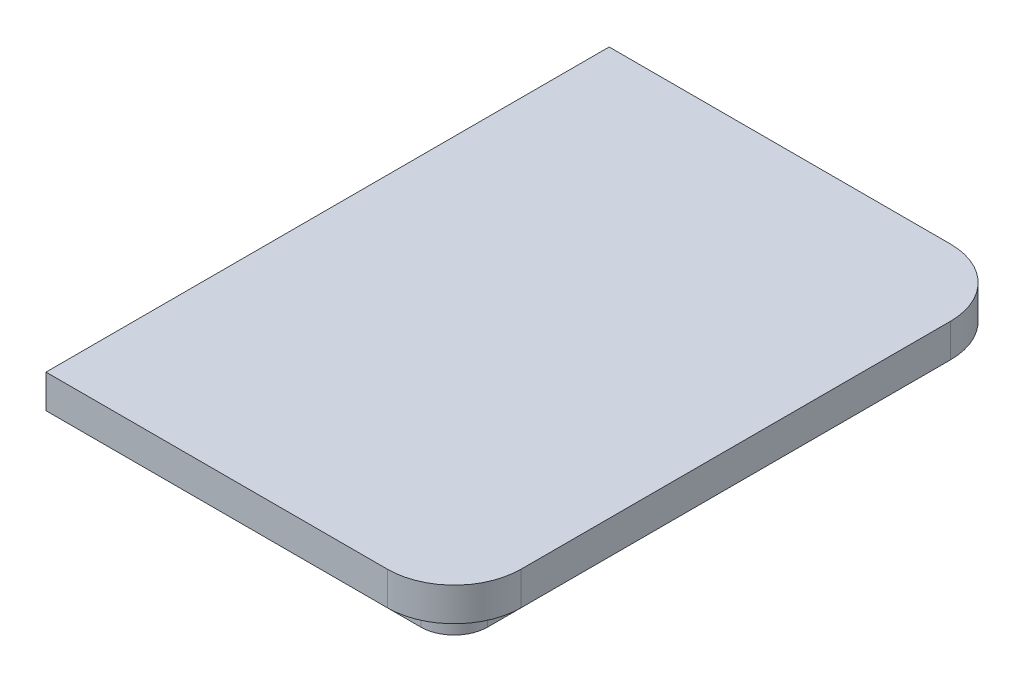
SolidWorks part; units mm, degrees
ref_plane "Alzado" through (0, 0, 0) normal (0, 0, 1) x (1, 0, 0)
ref_plane "Planta" through (0, 0, 0) normal (0, 1, 0) x (1, 0, 0)
ref_plane "Vista lateral" through (0, 0, 0) normal (1, 0, 0) x (0, 0, -1)
sketch "Croquis1" plane through (0, 0, 0) normal (0, 1, 0) x (1, 0, 0)
  line L1 (-30.5, -42.075) -> (20.5, -42.075)
  line L2 (-30.5, -42.075) -> (-30.5, 42.075)
  line L3 (-30.5, 42.075) -> (20.5, 42.075)
  line L4 (30.5, -32.075) -> (30.5, 32.075)
  line L5 (-30.5, -42.075) -> (30.5, 42.075) construction
  line L6 (-30.5, 42.075) -> (30.5, -42.075) construction
  arc A0 (20.5, -42.075) -> (30.5, -32.075) centre (20.5, -32.075) ccw
  arc A1 (30.5, 32.075) -> (20.5, 42.075) centre (20.5, 32.075) ccw
  point P0 (0, 0)
  dimension "D3" = 10
  dimension "D4" = 10
  dimension "D1" = 61
  dimension "D2" = 84.15
extrude "Saliente-Extruir1" add sketch "Croquis1" along normal blind 5
sketch "Croquis2" plane through (0, 0, 0) normal (0, 1, 0) x (1, 0, 0)
  line L4 (-30.5, -32.075) -> (20.5, -32.075)
  line L5 (20.5, -32.075) -> (20.5, 32.075)
  line L6 (20.5, 32.075) -> (-30.5, 32.075)
  line L7 (-30.5, 37.075) -> (-30.5, 32.075)
  line L12 (-30.5, -32.075) -> (-30.5, -37.075)
  line L29 (-25.5, 37.075) -> (-25.5, -37.075)
  line L30 (-25.5, -37.075) -> (20.5, -37.075)
  line L31 (25.5, -32.075) -> (25.5, 32.075)
  line L32 (20.5, 37.075) -> (-25.5, 37.075)
  line L34 (-30.5, -37.075) -> (20.5, -37.075)
  line L35 (25.5, -32.075) -> (25.5, 32.075)
  line L36 (20.5, 37.075) -> (-30.5, 37.075)
  arc A3 (20.5, -32.075) -> (20.5, -32.075) centre (20.5, -32.075) ccw
  arc A6 (20.5, 32.075) -> (20.5, 32.075) centre (20.5, 32.075) ccw
  arc A14 (20.5, -37.075) -> (25.5, -32.075) centre (20.5, -32.075) ccw
  arc A15 (25.5, 32.075) -> (20.5, 37.075) centre (20.5, 32.075) ccw
  arc A16 (20.5, -37.075) -> (25.5, -32.075) centre (20.5, -32.075) ccw
  arc A17 (25.5, 32.075) -> (20.5, 37.075) centre (20.5, 32.075) ccw
  dimension "D1" = 5
  dimension "D2" = 5
extrude "Saliente-Extruir2" add sketch "Croquis2" against normal blind 5
